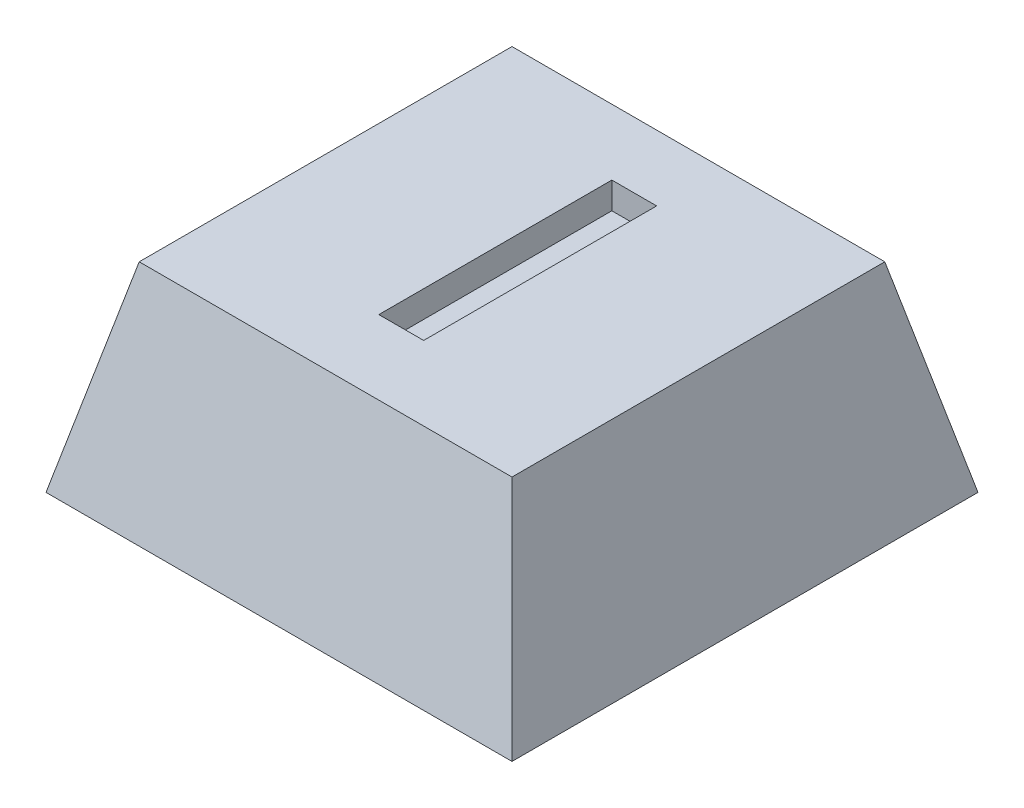
SolidWorks part; units mm, degrees
ref_plane "Front Plane" through (0, 0, 0) normal (0, 0, 1) x (1, 0, 0)
ref_plane "Top Plane" through (0, 0, 0) normal (0, 1, 0) x (1, 0, 0)
ref_plane "Right Plane" through (0, 0, 0) normal (1, 0, 0) x (0, 0, -1)
sketch "Sketch1" plane through (0, 0, 0) normal (0, 1, 0) x (1, 0, 0)
  line L1 (0, 0) -> (7, 0)
  line L2 (0, 0) -> (0, 7)
  line L3 (0, 7) -> (7, 7)
  line L4 (7, 0) -> (7, 7)
  dimension "D1" = 7
  dimension "D2" = 7
extrude "Boss-Extrude1" add sketch "Sketch1" along normal blind 3
sketch "Sketch2" plane through (0, 0, 0) normal (0, 0, 1) x (1, 0, 0)
  line L0 (0, 0) -> (0.7, 3)
  line L1 (0, 3) -> (7, 3) construction
  line L2 (0.7, 3) -> (0, 3)
  line L3 (0, 3) -> (0, 0)
  line L4 (7, 0) -> (6.3, 3)
  line L5 (6.3, 3) -> (7, 3)
  line L6 (7, 3) -> (7, 0)
  dimension "D1" = 0.7
  dimension "D2" = 0.7
extrude "Cut-Extrude1" cut sketch "Sketch2" against normal blind 7
sketch "Sketch3" plane through (0, 0, 0) normal (1, 0, 0) x (0, 0, -1)
  line L0 (0, 0) -> (0.7, 3)
  line L1 (7, 3) -> (0, 3) construction
  line L2 (0.7, 3) -> (0, 3)
  line L3 (0, 3) -> (0, 0)
  line L4 (7, 3) -> (6.3, 3)
  line L5 (6.3, 3) -> (7, 0)
  line L6 (7, 3) -> (7, 0)
  dimension "D1" = 0.7
  dimension "D2" = 0.7
extrude "Cut-Extrude2" cut sketch "Sketch3" along normal blind 11
sketch "Sketch4" plane through (0, 0, 0) normal (0, -1, 0) x (1, 0, 0)
  line L0 (3.5, 0) -> (3.5, -7) construction
  line L1 (0, 0) -> (7, 0) construction
  line L2 (7, -7) -> (0, -7) construction
  line L3 (0, -3.5) -> (7, -3.5) construction
  line L4 (0, -7) -> (0, 0) construction
  line L5 (7, 0) -> (7, -7) construction
  circle A0 centre (3.5, -3.5) radius 1.8
  dimension "D1" = 3.6
extrude "Cut-Extrude3" cut sketch "Sketch4" against normal blind 0.8
sketch "Sketch5" plane through (0, 3, 0) normal (0, 1, 0) x (1, 0, 0)
  text T0 "I" font "Arial" height 3.5
extrude "Cut-Extrude4" cut sketch "Sketch5" against normal blind 0.4
